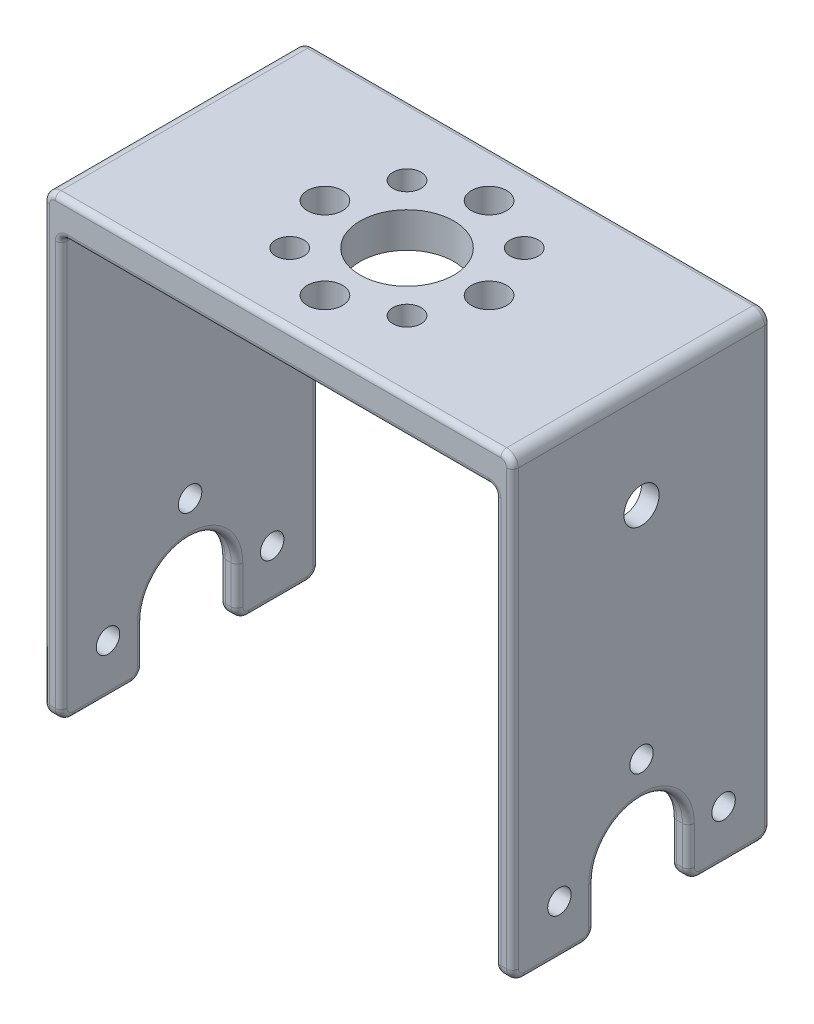
SolidWorks part; units mm, degrees
ref_plane "Front Plane" through (0, 0, 0) normal (0, 0, 1) x (1, 0, 0)
ref_plane "Top Plane" through (0, 0, 0) normal (0, 1, 0) x (1, 0, 0)
ref_plane "Right Plane" through (0, 0, 0) normal (1, 0, 0) x (0, 0, -1)
sketch "Sketch1" plane through (0, 0, 0) normal (0, 1, 0) x (1, 0, 0)
  line L1 (-20, 11) -> (20, 11)
  line L2 (-20, 11) -> (-20, -11)
  line L3 (-20, -11) -> (20, -11)
  line L4 (20, 11) -> (20, -11)
  line L5 (-20, 11) -> (20, -11) construction
  line L6 (-20, -11) -> (20, 11) construction
  circle A0 centre (0, 0) radius 4
  circle A1 centre (0, 7) radius 1.5
  circle A2 centre (7, 0) radius 1.5
  circle A3 centre (0, -7) radius 1.5
  circle A4 centre (-7, 0) radius 1.5
  circle A5 centre (5, 5) radius 1.2
  circle A6 centre (5, -5) radius 1.2
  circle A7 centre (-5, -5) radius 1.2
  circle A8 centre (-5, 5) radius 1.2
  point P0 (0, 0)
  point P19 (0, 0)
  point P28 (0, 0)
  dimension "D3" = 8
  dimension "D4" = 3
  dimension "D7" = 4
  dimension "D8" = 13
  dimension "D10" = 2.4
  dimension "D14" = 15
  dimension "D1" = 40
  dimension "D2" = 22
  dimension "D5" = 4
  dimension "D6" = 20
  dimension "D9" = 13
  dimension "D11" = 5
  dimension "D12" = 5
  dimension "D15" = 6
  dimension "D13" = 4
extrude "Boss-Extrude1" add sketch "Sketch1" along normal blind 3
sketch "Sketch2" plane through (0, 0, 0) normal (0, -1, 0) x (-1, 0, 0)
  line L0 (20, -11) -> (-20, -11) construction
  line L1 (-20, 11) -> (-18.5, 11)
  line L2 (-20, 11) -> (-20, -11)
  line L3 (-20, -11) -> (-18.5, -11)
  line L4 (-18.5, 11) -> (-18.5, -11)
  dimension "D1" = 1.5
extrude "Boss-Extrude2" add sketch "Sketch2" along normal blind 36
mirror "Mirror1" about plane through (0, 0, 0) normal (1, 0, 0) of "Boss-Extrude2"
fillet "Fillet1" radius 1 2 edges at (20, 3, 0) (-20, 3, 0)
sketch "Sketch3" plane through (-20, 0, 0) normal (-1, 0, 0) x (0, 0, 1)
  line L0 (-11, 2) -> (-11, -36) construction
  line L1 (-11, 3) -> (11, 3) construction
  line L2 (-4, -31.75) -> (-4, -36)
  line L11 (-11, -36) -> (11, -36) construction
  line L12 (4, -31.75) -> (4, -36)
  line L13 (11, 2) -> (11, -36) construction
  line L14 (4, -36) -> (-4, -36)
  circle A0 centre (0, -6) radius 1.5
  circle A1 centre (0, -24.75) radius 1
  circle A2 centre (-7, -31.75) radius 1
  circle A3 centre (7, -31.75) radius 1
  arc A4 (4, -31.75) -> (-4, -31.75) centre (0, -31.75) ccw
  dimension "D1" = 3
  dimension "D10" = 2
  dimension "D15" = 4
  dimension "D17" = 8
  dimension "D4" = 11.25
  dimension "D2" = 11
  dimension "D3" = 9
  dimension "D12" = 11
  dimension "D13" = 7
  dimension "D14" = 7
  dimension "D16" = 4
  dimension "D18" = 4.25
  dimension "D19" = 7
extrude "Cut-Extrude1" cut sketch "Sketch3" against normal through all
fillet "Fillet2" radius 1 8 edges at (-19.25, -36, 4) (-19.25, -36, 11) (-19.25, -36, -4) (-19.25, -36, -11) (19.25, -36, 11) (19.25, -36, 4) (19.25, -36, -4) (19.25, -36, -11)
fillet "圆角1" radius 0.5 54 edges at (-18.5, 0, 0) (-19.7071, 2.7071, -11) (-18.5, -17.5, 11) (-18.5, -17.5, -11) (-20, -35.7071, -10.7071) (-18.5, -35.7071, -10.7071) (-18.5, -36, -7.5) (-18.5, -35.7071, -4.2929) (-20, -36, -7.5) (-20, -35.7071, -4.2929) (-18.5, -33.375, -4) (-20, -33.375, -4) (-18.5, -35.7071, 4.2929) (-18.5, -33.375, 4) (-18.5, -27.75, 0) (-20, -27.75, 0) (-20, -33.375, 4) (-20, -35.7071, 4.2929) (-18.5, -35.7071, 10.7071) (-18.5, -36, 7.5) (-20, -35.7071, 10.7071) (-20, -36, 7.5) (-19.7071, 2.7071, 11) (-20, -16.5, 11) (-20, -16.5, -11) (0, 3, -11) (19.7071, 2.7071, -11) (20, -35.7071, -10.7071) (20, -16.5, -11) (20, -36, -7.5) (20, -35.7071, -4.2929) (20, -33.375, -4) (20, -27.75, 0) (20, -33.375, 4) (20, -35.7071, 4.2929) (20, -35.7071, 10.7071) (20, -36, 7.5) (18.5, -17.5, 11) (20, -16.5, 11) (19.7071, 2.7071, 11) (0, 3, 11) (0, 0, -11) (0, 0, 11) (18.5, 0, 0) (18.5, -35.7071, -10.7071) (18.5, -36, -7.5) (18.5, -35.7071, -4.2929) (18.5, -33.375, -4) (18.5, -27.75, 0) (18.5, -35.7071, 4.2929) (18.5, -33.375, 4) (18.5, -35.7071, 10.7071) (18.5, -36, 7.5) (18.5, -17.5, -11)
